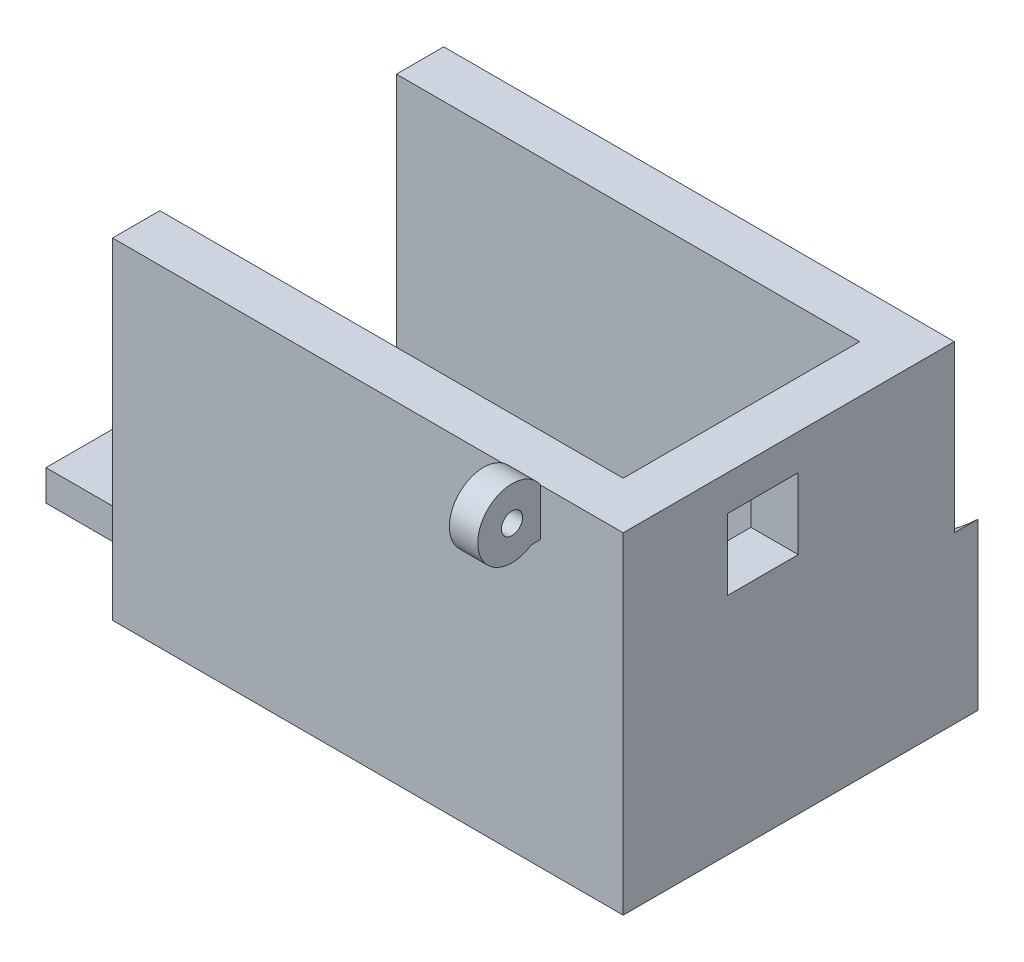
SolidWorks part; units mm, degrees
ref_plane "前基準面" through (0, 0, 0) normal (0, 0, 1) x (1, 0, 0)
ref_plane "上基準面" through (0, 0, 0) normal (0, 1, 0) x (1, 0, 0)
ref_plane "右基準面" through (0, 0, 0) normal (1, 0, 0) x (0, 0, -1)
sketch "草圖1" plane through (0, 0, 0) normal (0, 1, 0) x (1, 0, 0)
  line L1 (-203.3434, 62.6098) -> (162.5366, 62.6098)
  line L2 (-203.3434, 62.6098) -> (-203.3434, -77.3902)
  line L3 (-203.3434, -77.3902) -> (162.5366, -77.3902)
  line L4 (162.5366, 62.6098) -> (162.5366, -77.3902)
  dimension "D1" = 365.88
  dimension "D2" = 140
extrude "填料-伸長1" add sketch "草圖1" along normal blind 140
sketch "草圖2" plane through (0, 140, 0) normal (0, 1, 0) x (1, 0, 0)
  line L0 (-203.3434, 62.6098) -> (-203.3434, -77.3902) construction
  line L1 (-203.3434, 42.6098) -> (142.5366, 42.6098)
  line L2 (-203.3434, 42.6098) -> (-203.3434, -57.3902)
  line L3 (-203.3434, -57.3902) -> (142.5366, -57.3902)
  line L4 (142.5366, 42.6098) -> (142.5366, -57.3902)
  line L5 (162.5366, 62.6098) -> (-203.3434, 62.6098) construction
  line L6 (-203.3434, -77.3902) -> (162.5366, -77.3902) construction
  line L7 (162.5366, -77.3902) -> (162.5366, 62.6098) construction
  dimension "D1" = 20
  dimension "D2" = 20
  dimension "D3" = 20
extrude "除料-伸長1" cut sketch "草圖2" against normal blind 110
sketch "草圖8" plane through (0, 0, 77.3902) normal (0, 0, 1) x (1, 0, 0)
  line L0 (162.5366, 140) -> (162.5366, 0) construction
  line L1 (115.5366, 132) -> (127.5366, 132)
  line L2 (115.5366, 132) -> (115.5366, 120)
  line L3 (115.5366, 120) -> (127.5366, 120)
  line L4 (127.5366, 132) -> (127.5366, 120)
  line L5 (-203.3434, 140) -> (162.5366, 140) construction
  dimension "D1" = 35
  dimension "D2" = 8
  dimension "D3" = 12
  dimension "D4" = 12
extrude "填料-伸長2" add sketch "草圖8" along normal blind 10
sketch "草圖9" plane through (127.5366, 0, 0) normal (1, 0, 0) x (0, 0, -1)
  line L0 (-87.3902, 132) -> (-89.3902, 132) construction
  circle A0 centre (-89.3902, 132) radius 4.49
  dimension "D1" = 8.98
extrude "伸長-薄件1" add sketch "草圖9" against normal blind 12 thin
sketch "草圖11" plane through (127.5366, 0, 0) normal (1, 0, 0) x (0, 0, -1)
  line L0 (-1093.8802, 132) -> (48906.1198, 132) construction
  line L1 (-89.3902, -872.49) -> (-89.3902, 49127.51) construction
  circle A2 centre (-89.3902, 132) radius 4.49
  dimension "D1" = 8.98
extrude "除料-伸長5" cut sketch "草圖11" against normal through all
sketch "草圖13" plane through (0, 140, 0) normal (0, 1, 0) x (1, 0, 0)
  line L0 (162.5366, 62.6098) -> (-203.3434, 62.6098) construction
  line L1 (-203.3434, -77.3902) -> (-53.3434, -77.3902)
  line L2 (-203.3434, -77.3902) -> (-203.3434, 62.6098)
  line L3 (-203.3434, 62.6098) -> (-53.3434, 62.6098)
  line L4 (-53.3434, -77.3902) -> (-53.3434, 62.6098)
  dimension "D1" = 150
extrude "除料-伸長7" cut sketch "草圖13" against normal through all
sketch "草圖14" plane through (-53.3434, 0, 0) normal (-1, 0, 0) x (0, 0, 1)
  line L0 (-62.6098, 0) -> (-62.6098, 140) construction
  line L1 (-42.6098, 20) -> (55.5296, 20)
  line L2 (-42.6098, 20) -> (-42.6098, 7)
  line L3 (-42.6098, 7) -> (55.5296, 7)
  line L4 (55.5296, 20) -> (55.5296, 7)
  line L5 (57.3902, 30) -> (-42.6098, 30) construction
  line L6 (77.3902, 0) -> (-62.6098, 0) construction
  dimension "D1" = 20
  dimension "D2" = 10
  dimension "D3" = 7
extrude "填料-伸長3" add sketch "草圖14" along normal blind 50
sketch "草圖15" plane through (0, 20, 0) normal (0, 1, 0) x (1, 0, 0)
  line L0 (-53.3434, -7.3902) -> (10.5366, -7.3902) construction
  line L1 (-53.3434, -57.3902) -> (-53.3434, 42.6098) construction
  circle A0 centre (10.5366, -7.3902) radius 3
  dimension "D1" = 6
extrude "除料-伸長8" cut sketch "草圖15" against normal through all
sketch "草圖16" plane through (0, 0, -62.6098) normal (0, 0, -1) x (-1, 0, 0)
  line L0 (53.3434, 140) -> (53.3434, 82.32) construction
  line L1 (53.3434, 0) -> (53.3434, 140) construction
  line L2 (-162.5366, 140) -> (-162.5366, 0) construction
  line L3 (-162.5366, 70) -> (-162.5366, 0)
  line L4 (-162.5366, 0) -> (53.3434, 0)
  line L5 (53.3434, 0) -> (53.3434, 82.32)
  spline S0 degree 3 poles (53.3434, 82.32) (-56.1531, 198.1609) (-74.6423, -13.8218) (-162.5366, 70) knots 0 0 0 0 1 1 1 1
extrude "填料-伸長4" add sketch "草圖16" along normal blind 10
sketch "草圖20" plane through (142.5366, 0, 0) normal (-1, 0, 0) x (0, 0, 1)
  line L0 (-7.0138, 30) -> (-7.0138, 95) construction
  line L1 (57.3902, 30) -> (-42.6098, 30) construction
sketch "草圖22" plane through (142.5366, 0, 0) normal (-1, 0, 0) x (0, 0, 1)
  line L0 (57.3902, 140) -> (-42.6098, 140) construction
  line L1 (3.3902, 95) -> (33.3902, 95)
  line L2 (-7.0138, 95) -> (3.3902, 95) construction
  line L3 (3.3902, 95) -> (3.3902, 140)
  line L4 (3.3902, 140) -> (33.3902, 140)
  line L5 (33.3902, 95) -> (33.3902, 140)
  dimension "D1" = 30
extrude "除料-伸長9" cut sketch "草圖22" against normal through all
sketch "草圖26" plane through (0, 0, 3.3902) normal (0, 0, 1) x (1, 0, 0)
  line L0 (162.5366, 95) -> (162.5366, 125) construction
  line L1 (162.5366, 140) -> (162.5366, 95) construction
  line L3 (162.5366, 125) -> (142.5366, 125)
  line L4 (162.5366, 125) -> (162.5366, 140)
  line L5 (162.5366, 140) -> (142.5366, 140)
  line L6 (142.5366, 125) -> (142.5366, 140)
extrude "填料-伸長6" add sketch "草圖26" along normal blind 40
sketch "草圖30" plane through (0, 20, 0) normal (0, 1, 0) x (1, 0, 0)
  line L0 (-53.3434, -7.3902) -> (-83.3434, -7.3902) construction
  line L1 (-53.3434, -57.3902) -> (-53.3434, 42.6098) construction
  circle A0 centre (-83.3434, -7.3902) radius 3
  dimension "D1" = 6
extrude "除料-伸長10" cut sketch "草圖30" against normal through all
